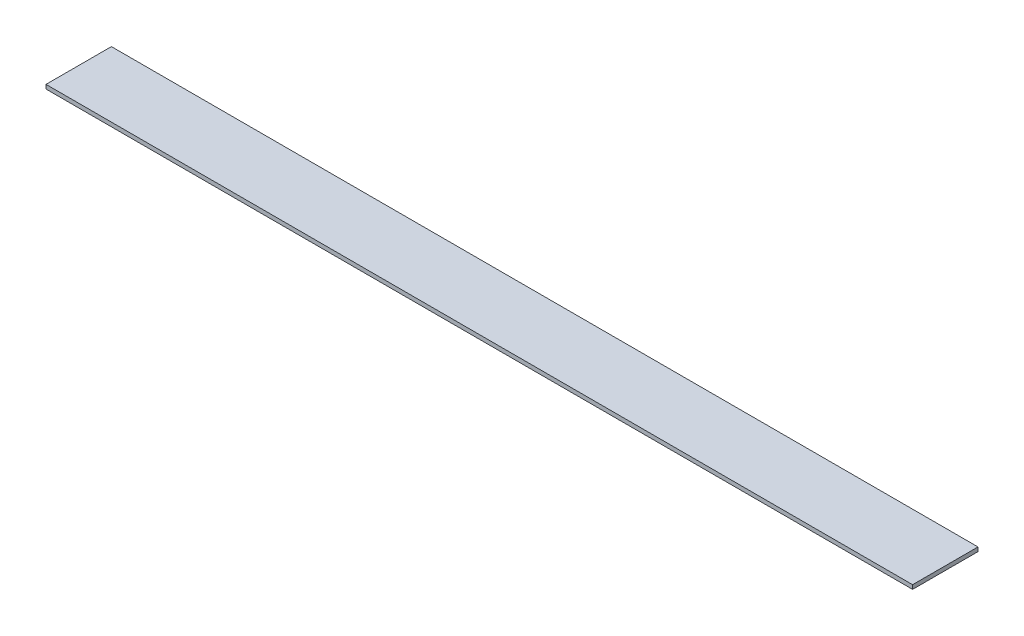
SolidWorks part; units mm, degrees
material "Nylon 101"
ref_plane "Front Plane" through (0, 0, 0) normal (0, 0, 1) x (1, 0, 0)
ref_plane "Top Plane" through (0, 0, 0) normal (0, 1, 0) x (1, 0, 0)
ref_plane "Right Plane" through (0, 0, 0) normal (1, 0, 0) x (0, 0, -1)
sketch "Sketch1" plane through (0, 0, 0) normal (0, 1, 0) x (1, 0, 0)
  line L1 (0, 0) -> (336.55, 0)
  line L2 (0, 0) -> (0, 25.4)
  line L3 (0, 25.4) -> (336.55, 25.4)
  line L4 (336.55, 0) -> (336.55, 25.4)
  dimension "D1" = 25.4
  dimension "D2" = 336.55
extrude "Boss-Extrude1" add sketch "Sketch1" along normal blind 1.5875
